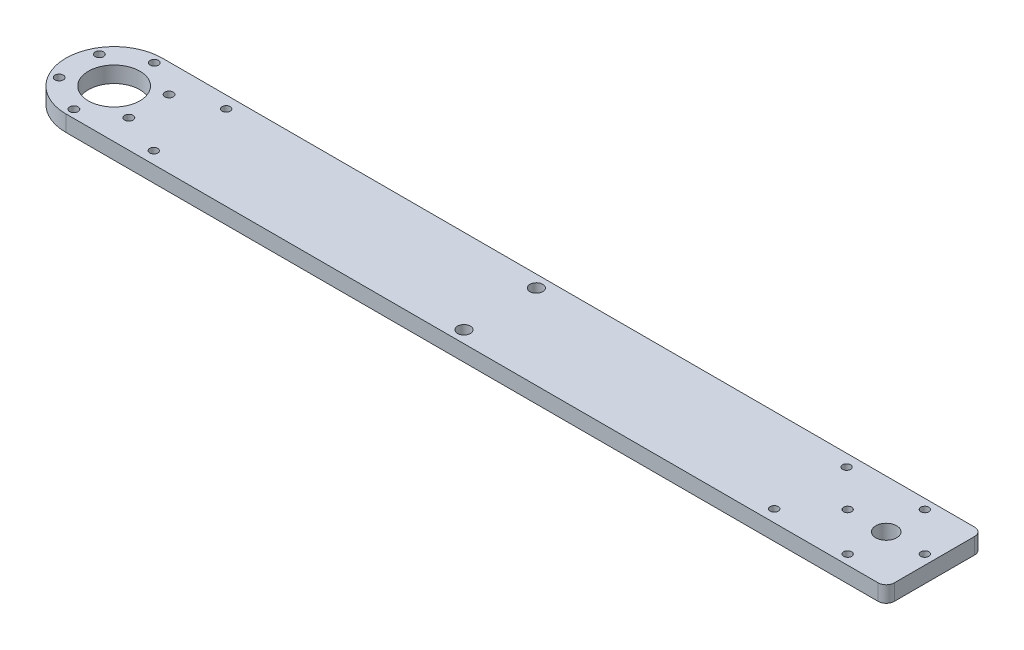
SolidWorks part; units mm, degrees
material "Nylon 101"
ref_plane "Alzado" through (0, 0, 0) normal (0, 0, 1) x (1, 0, 0)
ref_plane "Planta" through (0, 0, 0) normal (0, 1, 0) x (1, 0, 0)
ref_plane "Vista lateral" through (0, 0, 0) normal (1, 0, 0) x (0, 0, -1)
sketch "Croquis1" plane through (0, 0, 0) normal (0, 1, 0) x (1, 0, 0)
  line L0 (-250, 0) -> (250, 0) construction
  line L1 (-250, 30) -> (250, 30)
  line L2 (-250, -30) -> (250, -30)
  line L3 (280, 0) -> (280, 30)
  line L4 (280, 30) -> (250, 30)
  line L5 (280, 0) -> (280, -30)
  line L6 (280, -30) -> (250, -30)
  arc A0 (-250, 30) -> (-250, -30) centre (-250, 0) ccw
  point P2 (0, 0)
  point P10 (0, 30)
  point P11 (0, -30)
  dimension "D3" = 30
  dimension "D1" = 500
  dimension "D2" = 60
  dimension "D4" = 530
extrude "Saliente-Extruir1" add sketch "Croquis1" along normal mid plane 10
sketch "Croquis2" plane through (0, 5, 0) normal (0, 1, 0) x (1, 0, 0)
  circle A0 centre (-250, 0) radius 16
  dimension "D1" = 32
extrude "Cortar-Extruir1" cut sketch "Croquis2" against normal blind 10
sketch "Croquis4" plane through (0, 5, 0) normal (0, 1, 0) x (1, 0, 0)
  circle A0 centre (-250, 0) radius 25 construction
  circle A1 centre (-250, 25) radius 2.6
  dimension "D1" = 50
  dimension "D2" = 5.2
extrude "Cortar-Extruir2" cut sketch "Croquis4" against normal blind 10
pattern_circular "MatrizC1" count 6 over 360 about axis through (-250, 0, 0) along (0, 1, 0) of "Cortar-Extruir2"
fillet "Redondeo1" radius 10 2 edges at (280, 0, 30) (280, 0, -30)
sketch "Croquis5" plane through (0, 5, 0) normal (0, 1, 0) x (1, 0, 0)
  circle A0 centre (230, 0) radius 16
  circle A1 centre (-250, 0) radius 16 construction
  dimension "D1" = 32
  dimension "D2" = 480
extrude "Cortar-Extruir3" cut sketch "Croquis5" against normal through all
sketch "Croquis6" plane through (0, 5, 0) normal (0, 1, 0) x (1, 0, 0)
  line L0 (-250, -30) -> (270, -30) construction
  line L4 (260, 30) -> (260, -30)
  line L7 (280, -20) -> (280, 20) construction
  line L8 (270, 30) -> (-250, 30) construction
  line L9 (260, -30) -> (270, -30)
  line L10 (280, -20) -> (280, 20)
  line L11 (270, 30) -> (260, 30)
  arc A0 (270, -30) -> (280, -20) centre (270, -20) ccw construction
  arc A1 (280, 20) -> (270, 30) centre (270, 20) ccw construction
  arc A2 (270, -30) -> (280, -20) centre (270, -20) ccw
  arc A3 (280, 20) -> (270, 30) centre (270, 20) ccw
  point P0 (230, 0)
  dimension "D1" = 20
extrude "Cortar-Extruir4" cut sketch "Croquis6" against normal through all
fillet "Redondeo2" radius 5 2 edges at (260, 0, 30) (260, 0, -30)
sketch "Croquis7" plane through (0, -5, 0) normal (0, -1, 0) x (1, 0, 0)
  line L0 (230, 0) -> (182.85, 0) construction
  line L1 (182.85, 22.5) -> (182.85, -22.5) construction
  circle A0 centre (182.85, -22.5) radius 2.5
  circle A1 centre (182.85, 22.5) radius 2.5
  point P7 (182.85, 0)
  dimension "D3" = 5
  dimension "D1" = 47.15
  dimension "D2" = 45
extrude "Cortar-Extruir5" cut sketch "Croquis7" against normal blind 10
sketch "Croquis8" plane through (0, -5, 0) normal (0, -1, 0) x (1, 0, 0)
  line L0 (-250, 0) -> (-202.85, 0) construction
  line L1 (-202.85, 22.5) -> (-202.85, -22.5) construction
  circle A0 centre (-202.85, -22.5) radius 2.5
  circle A1 centre (-202.85, 22.5) radius 2.5
  point P6 (-202.85, 0)
  dimension "D3" = 5
  dimension "D1" = 47.15
  dimension "D2" = 45
extrude "Cortar-Extruir6" cut sketch "Croquis8" against normal through all
sketch "Sketch1" plane through (0, -5, 0) normal (0, -1, 0) x (-1, 0, 0)
  line L0 (202.85, -22.5) -> (-182.85, -22.5)
  line L1 (10, -22.5) -> (30, -22.5)
  line L2 (10, -22.5) -> (-10, -22.5)
  circle A2 centre (10, -22.5) radius 4
  dimension "D1" = 8
extrude "Cut-Extrude1" cut sketch "Sketch1" against normal blind 10
mirror "Mirror1" about plane through (0, 0, 0) normal (0, 0, 1) of "Cut-Extrude1"
sketch "Sketch2" plane through (0, 5, 0) normal (0, 1, 0) x (1, 0, 0)
  line L0 (230, 0) -> (230, 24)
  circle A0 centre (230, 24) radius 2.5
  dimension "D1" = 5
  dimension "D2" = 24
extrude "Cut-Extrude2" cut sketch "Sketch2" against normal through all
pattern_circular "CirPattern1" count 4 over 360 about axis through (230, 0, 0) along (0, 1, 0) of "Cut-Extrude2"
sketch "Sketch3" plane through (0, 5, 0) normal (0, 1, 0) x (1, 0, 0)
  circle A0 centre (230, 0) radius 16
  circle A1 centre (230, 0) radius 16 construction
  circle A2 centre (230, 0) radius 6.5
  dimension "D1" = 13
extrude "Boss-Extrude1" add sketch "Sketch3" against normal blind 10
